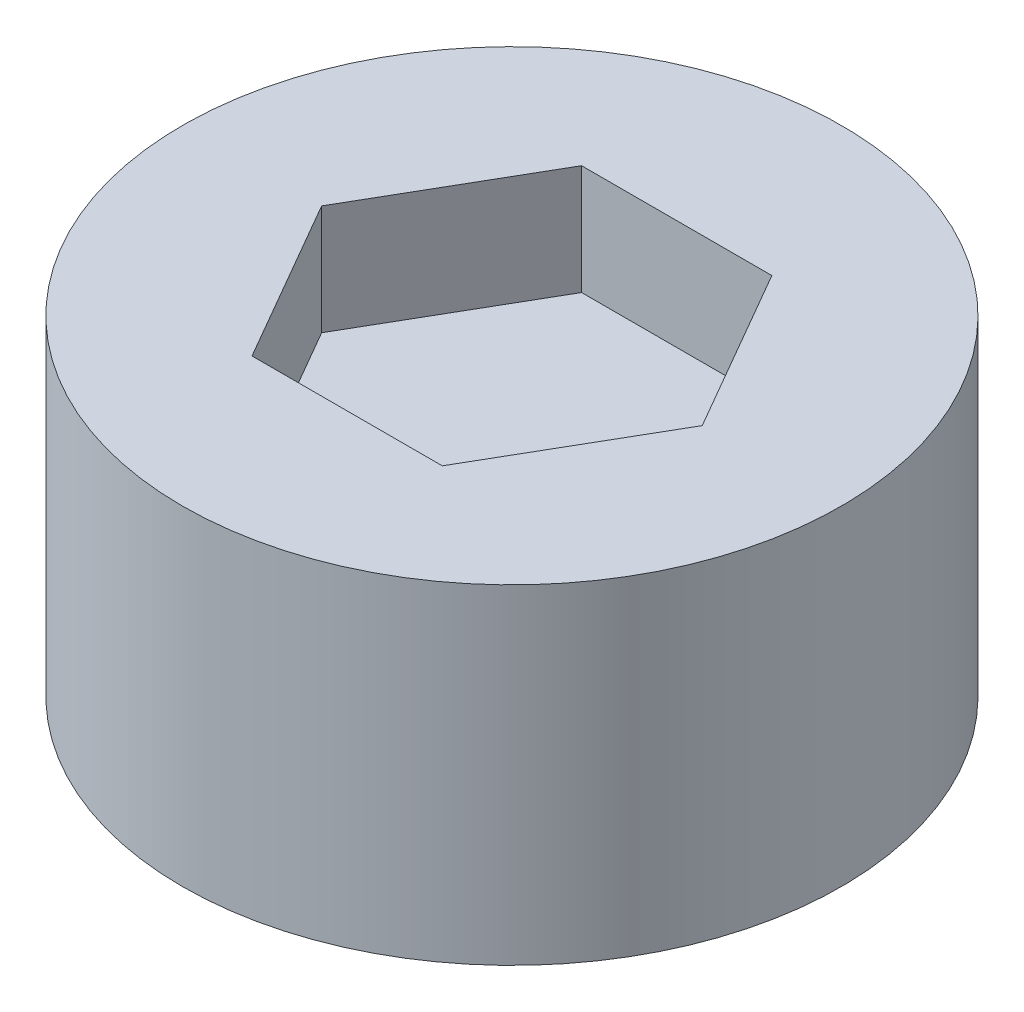
SolidWorks part; units mm, degrees
ref_plane "前视基准面" through (0, 0, 0) normal (0, 0, 1) x (1, 0, 0)
ref_plane "上视基准面" through (0, 0, 0) normal (0, 1, 0) x (1, 0, 0)
ref_plane "右视基准面" through (0, 0, 0) normal (1, 0, 0) x (0, 0, -1)
other "Configuration Table"
sketch "草图1" plane through (0, 0, 0) normal (0, 1, 0) x (1, 0, 0)
  circle A0 centre (0, 0) radius 1.5
  dimension "D1" = 3
extrude "凸台-拉伸1" add sketch "草图1" against normal blind 1.5
sketch "草图2" plane through (0, 0, 0) normal (0, 1, 0) x (1, 0, 0)
  line L1 (0.433, -0.75) -> (0.866, 0)
  line L2 (0.866, 0) -> (0.433, 0.75)
  line L3 (0.433, 0.75) -> (-0.433, 0.75)
  line L4 (-0.433, 0.75) -> (-0.866, 0)
  line L5 (-0.866, 0) -> (-0.433, -0.75)
  line L6 (-0.433, -0.75) -> (0.433, -0.75)
  circle A0 centre (0, 0) radius 0.75 construction
  dimension "D1" = 1.5
extrude "切除-拉伸1" cut sketch "草图2" against normal blind 0.5
